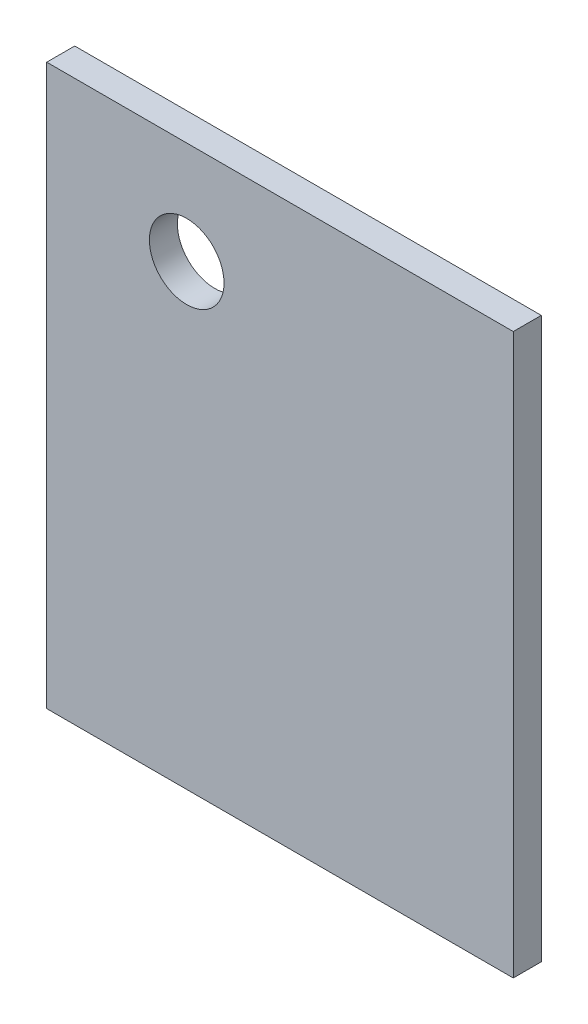
SolidWorks part; units mm, degrees
ref_plane "Front Plane" through (0, 0, 0) normal (0, 0, 1) x (1, 0, 0)
ref_plane "Top Plane" through (0, 0, 0) normal (0, 1, 0) x (1, 0, 0)
ref_plane "Right Plane" through (0, 0, 0) normal (1, 0, 0) x (0, 0, -1)
sketch "Sketch1" plane through (0, 0, 0) normal (0, 0, 1) x (1, 0, 0)
  line L1 (-25, -30) -> (25, -30)
  line L2 (-25, -30) -> (-25, 30)
  line L3 (-25, 30) -> (25, 30)
  line L4 (25, -30) -> (25, 30)
  line L5 (-25, -30) -> (25, 30) construction
  line L6 (-25, 30) -> (25, -30) construction
  circle A0 centre (-10, 19) radius 4
  point P0 (0, 0)
  dimension "D3" = 11
  dimension "D1" = 60
  dimension "D2" = 50
  dimension "D4" = 15
extrude "Boss-Extrude1" add sketch "Sketch1" along normal blind 3
